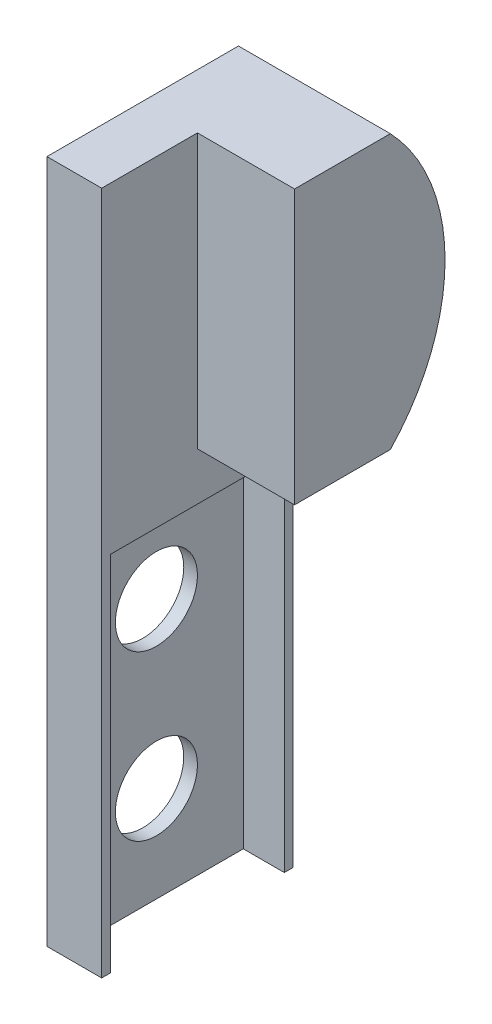
SolidWorks part; units mm, degrees
ref_plane "Alzado" through (0, 0, 0) normal (0, 0, 1) x (1, 0, 0)
ref_plane "Planta" through (0, 0, 0) normal (0, 1, 0) x (1, 0, 0)
ref_plane "Vista lateral" through (0, 0, 0) normal (1, 0, 0) x (0, 0, -1)
sketch "Croquis1" plane through (0, 0, 0) normal (1, 0, 0) x (0, 0, -1)
  line L1 (0, 0) -> (-14, 0)
  line L2 (0, 0) -> (0, -50)
  line L3 (0, -50) -> (-14, -50)
  line L4 (-14, 0) -> (-14, -50)
  dimension "D1" = 14
  dimension "D2" = 50
extrude "Saliente-Extruir1" add sketch "Croquis1" along normal blind 4 contours L2 L3 L4 L1
sketch "Croquis2" plane through (0, -50, 0) normal (0, -1, 0) x (1, 0, 0)
  line L0 (2, 14) -> (2, 13.35) construction
  line L1 (4, 14) -> (0, 14) construction
  line L2 (4, 13.35) -> (1, 13.35)
  line L3 (4, 0) -> (4, 14) construction
  line L4 (1, 13.35) -> (1, 0.65)
  line L5 (0, 0) -> (0, 14) construction
  line L6 (1, 7) -> (0, 7) construction
  line L7 (4, 0.65) -> (1, 0.65)
  line L8 (4, 13.35) -> (4, 0.65)
  dimension "D1" = 1
  dimension "D2" = 0.65
extrude "Cortar-Extruir1" cut sketch "Croquis2" against normal blind 26.5 contours L4 L7 L8 L2
sketch "Croquis3" plane through (4, 0, 0) normal (1, 0, 0) x (0, 0, -1)
  line L0 (-14, 0) -> (-7, 0) construction
  line L1 (0, 0) -> (-14, 0) construction
  line L2 (-7, 0) -> (-7, -20)
  line L3 (-7, -20) -> (0, -20)
  line L4 (0, 0) -> (0, -50) construction
  line L5 (0, -20) -> (0, -10)
  line L6 (0, 0) -> (-7, 0)
  line L7 (0, -10) -> (4, -10) construction
  arc A0 (0, 0) -> (0, -20) centre (-10.5, -10) cw
  line M13 (0, -50) -> (0, 0)
  line M14 (0, 0) -> (-14, 0)
  dimension "D1" = 20
  dimension "D2" = 4
extrude "Saliente-Extruir2" add sketch "Croquis3" along normal blind 7.1 contours A0 M13 | L2 L3 M13 M14
sketch "Croquis4" plane through (1, 0, 0) normal (1, 0, 0) x (0, 0, -1)
  line L0 (-7, -50) -> (-7, -43) construction
  line L1 (-13.35, -50) -> (-0.65, -50) construction
  line L2 (-7, -43) -> (-7, -31) construction
  circle A0 centre (-7, -31) radius 3
  circle A1 centre (-7, -43) radius 3
  dimension "D1" = 7
  dimension "D2" = 12
extrude "Cortar-Extruir2" cut sketch "Croquis4" against normal up to next
